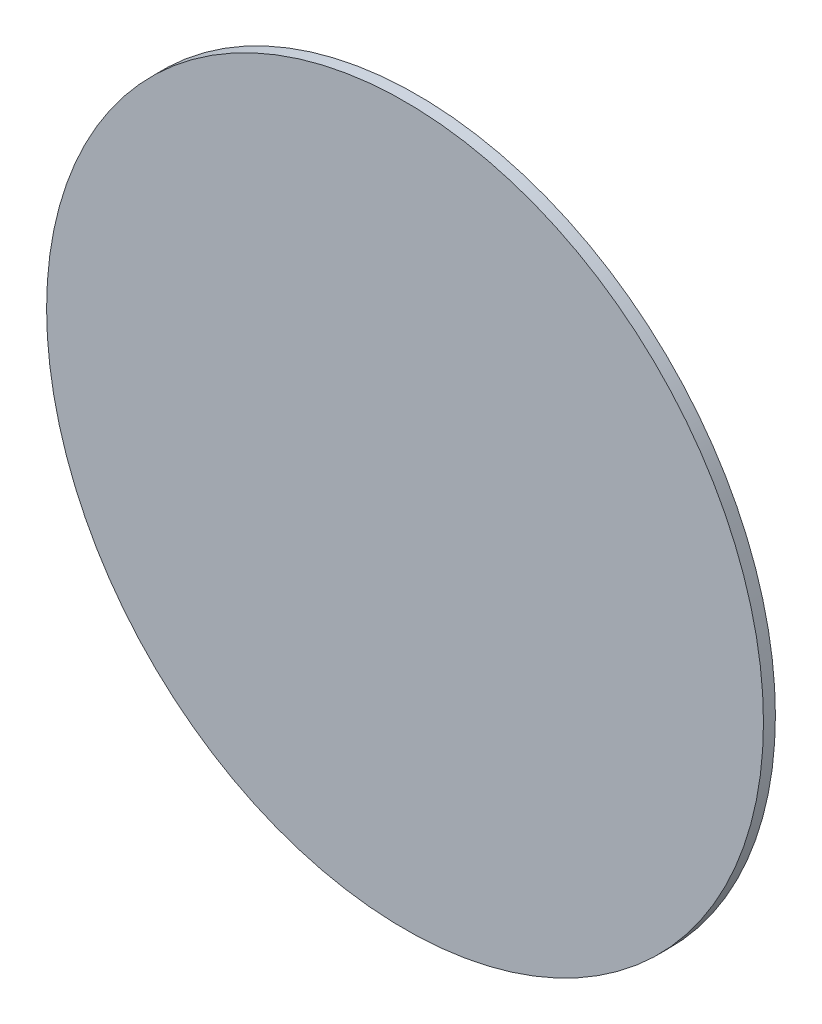
SolidWorks part; units mm, degrees
ref_plane "Front Plane" through (0, 0, 0) normal (0, 0, 1) x (1, 0, 0)
ref_plane "Top Plane" through (0, 0, 0) normal (0, 1, 0) x (1, 0, 0)
ref_plane "Right Plane" through (0, 0, 0) normal (1, 0, 0) x (0, 0, -1)
sketch "Sketch1" plane through (0, 0, 0) normal (0, 0, 1) x (1, 0, 0)
  circle A0 centre (16.024, 22.1545) radius 76.2
  circle A1 centre (16.024, 22.1545) radius 76.2 construction
extrude "Boss-Extrude1" add sketch "Sketch1" along normal blind 2.54
